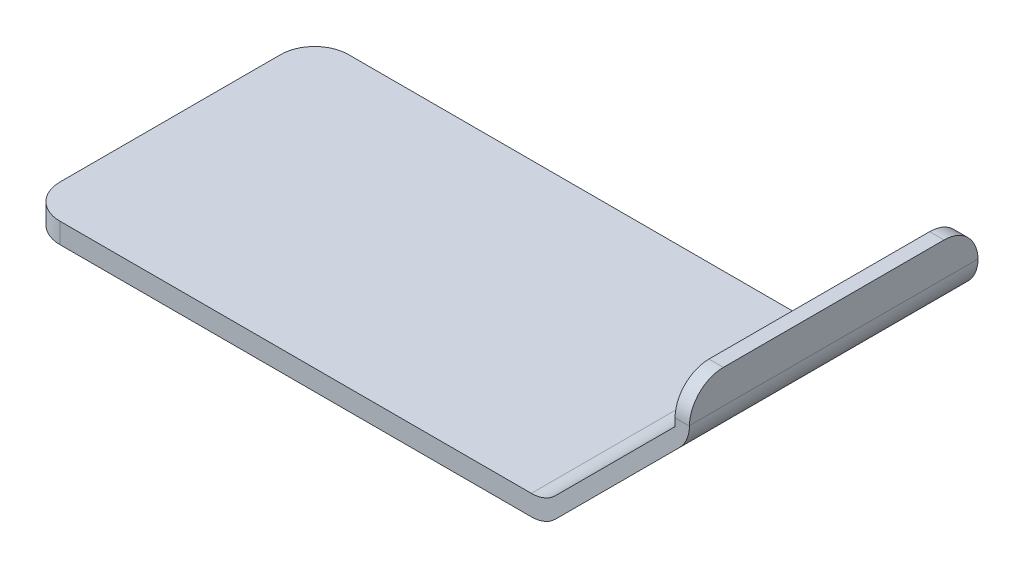
SolidWorks part; units mm, degrees
ref_plane "Front Plane" through (0, 0, 0) normal (0, 0, 1) x (1, 0, 0)
ref_plane "Top Plane" through (0, 0, 0) normal (0, 1, 0) x (1, 0, 0)
ref_plane "Right Plane" through (0, 0, 0) normal (1, 0, 0) x (0, 0, -1)
sketch "Sketch1" plane through (0, 0, 0) normal (0, 1, 0) x (1, 0, 0)
  line L1 (0, 0) -> (76.5, 0)
  line L2 (0, 0) -> (0, 42.5)
  line L3 (0, 42.5) -> (76.5, 42.5)
  line L4 (76.5, 0) -> (76.5, 42.5)
  dimension "D1" = 76.5
  dimension "D2" = 42.5
extrude "Boss-Extrude1" add sketch "Sketch1" along normal blind 3
sketch "Sketch2" plane through (0, 0, 0) normal (0, 0, 1) x (1, 0, 0)
  line L0 (76.5, 3) -> (76.5, 0)
  line L1 (95.5919, 28.2132) -> (97.7132, 28.2132)
  line L3 (76.5, 0) -> (97.7132, 21.2132)
  line L4 (76.5, 3) -> (95.5919, 22.0919)
  line L5 (97.7132, 21.2132) -> (97.7132, 28.2132)
  line L6 (95.5919, 22.0919) -> (95.5919, 28.2132)
extrude "Boss-Extrude2" add sketch "Sketch2" against normal blind 42.5
fillet "Fillet1" radius 5 2 edges at (97.7132, 21.2132, -21.25) (76.5, 0, -21.25)
fillet "Fillet2" radius 5 2 edges at (0, 1.5, -42.5) (0, 1.5, 0)
fillet "Fillet3" radius 5 2 edges at (96.6525, 28.2132, 0) (96.6525, 28.2132, -42.5)
fillet "Fillet4" radius 5 1 edges at (76.5, 3, -21.25)
